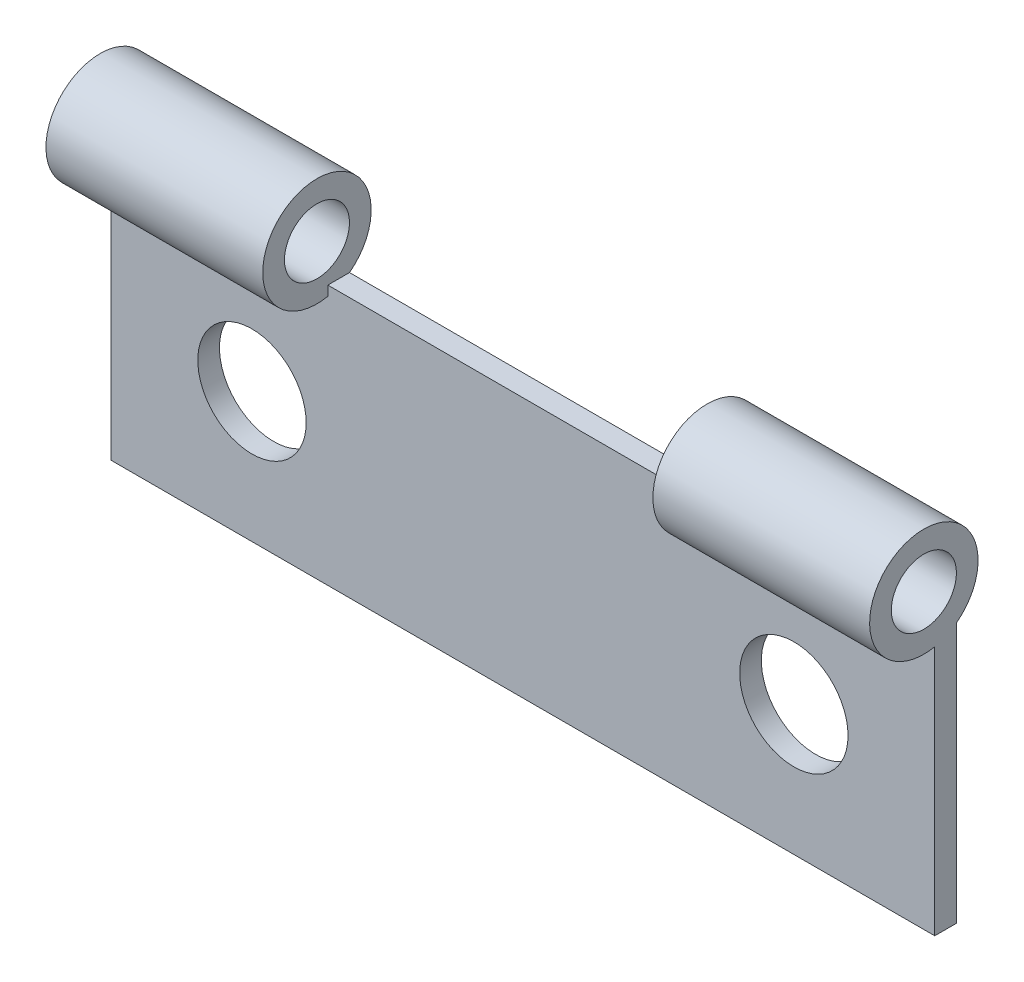
SolidWorks part; units mm, degrees
ref_plane "Front" through (0, 0, 0) normal (0, 0, 1) x (1, 0, 0)
ref_plane "Top" through (0, 0, 0) normal (0, 1, 0) x (1, 0, 0)
ref_plane "Right" through (0, 0, 0) normal (1, 0, 0) x (0, 0, -1)
sketch "草图1" plane through (0, 0, 0) normal (0, 0, 1) x (1, 0, 0)
  line L1 (-19, -6) -> (19, -6)
  line L2 (-19, -6) -> (-19, 6)
  line L3 (-19, 6) -> (19, 6)
  line L4 (19, -6) -> (19, 6)
  line L5 (-19, -6) -> (19, 6) construction
  line L6 (-19, 6) -> (19, -6) construction
  circle A0 centre (12.5, 0) radius 2.5
  circle A1 centre (-12.5, 0) radius 2.5
  point P0 (0, 0)
  dimension "D1" = 12
  dimension "D2" = 38
extrude "凸台-拉伸1" add sketch "草图1" along normal blind 1
ref_plane "基准面1" through (-9, 0, 0) normal (-1, 0, 0) x (0, 0, 1)
sketch "草图3" plane through (-9, 0, 0) normal (-1, 0, 0) x (0, 0, 1)
  circle A0 centre (1.5018, 8.0018) radius 2.5018
  circle A1 centre (1.5018, 8.0018) radius 1.5
extrude "凸台-拉伸4" add sketch "草图3" along normal blind 10
ref_plane "基准面2" through (9, 0, 0) normal (1, 0, 0) x (0, 0, -1)
sketch "草图4" plane through (9, 0, 0) normal (1, 0, 0) x (0, 0, -1)
  circle A0 centre (-1.5018, 8.0018) radius 1.5018
  circle A1 centre (-1.5018, 8.0018) radius 2.5018
extrude "凸台-拉伸5" add sketch "草图4" along normal blind 10
move or copy body "实体-移动/复制1" [suppressed] bodies to move or copy 105
